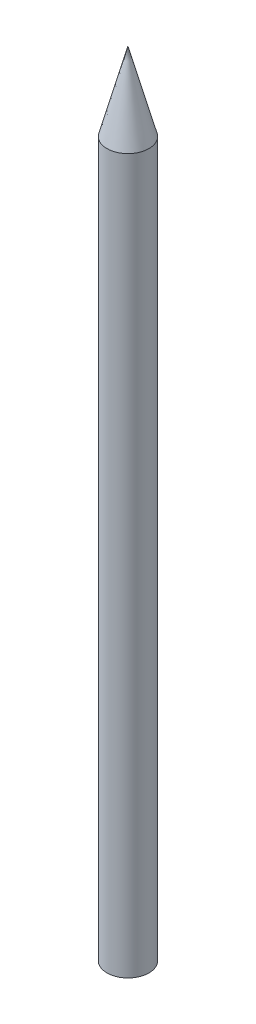
SolidWorks part; units mm, degrees
material "Nickel silver 65-12, UNS C75700"
ref_plane "Front" through (0, 0, 0) normal (0, 0, 1) x (1, 0, 0)
ref_plane "Top" through (0, 0, 0) normal (0, 1, 0) x (1, 0, 0)
ref_plane "Right" through (0, 0, 0) normal (1, 0, 0) x (0, 0, -1)
sketch "Sketch1" plane through (0, 0, 0) normal (1, 0, 0) x (0, 0, -1)
  line L12 (0, 0) -> (0, -10)
  line L13 (0, -10) -> (0.265, -10)
  line L14 (0.265, -10) -> (0.265, -0.989)
  line L15 (0.265, -0.989) -> (0, 0)
  dimension "D1" = 15
  dimension "D2" = 0.265
  dimension "D3" = 10
revolve "Revolve1" add sketch "Sketch1" angle 360 about L12
equation "\"D2@Sketch1\"=0.53/2"
